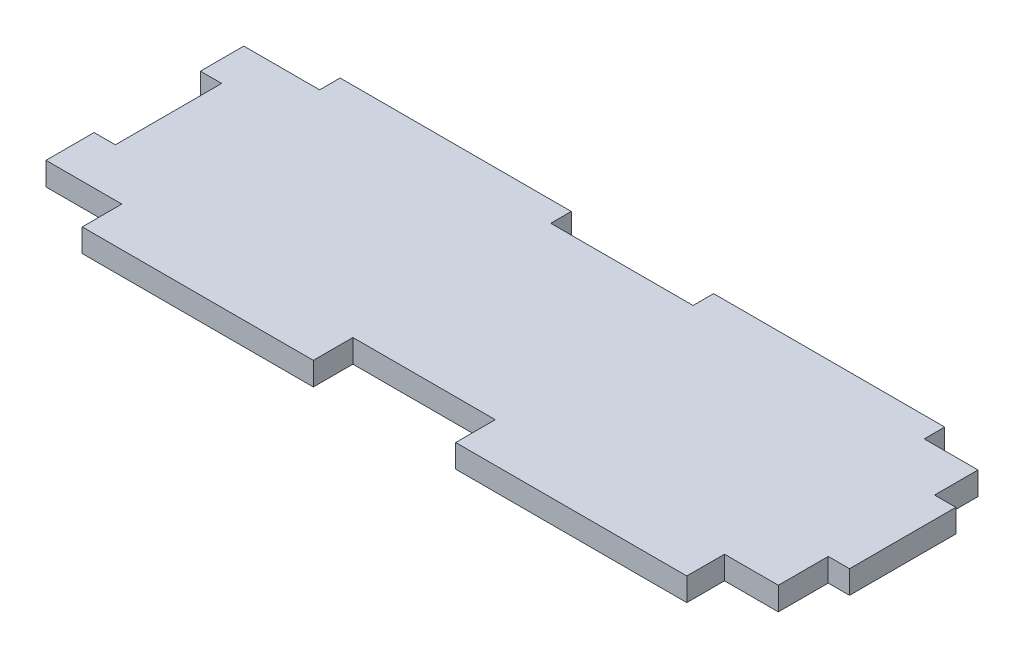
SolidWorks part; units mm, degrees
ref_plane "Front Plane" through (0, 0, 0) normal (0, 0, 1) x (1, 0, 0)
ref_plane "Top Plane" through (0, 0, 0) normal (0, 1, 0) x (1, 0, 0)
ref_plane "Right Plane" through (0, 0, 0) normal (1, 0, 0) x (0, 0, -1)
sketch "Sketch1" plane through (0, 0, 0) normal (0, 1, 0) x (1, 0, 0)
  line L0 (-49.022, -7.3025) -> (-49.022, 7.3025)
  line L1 (-49.022, 7.3025) -> (-51.943, 7.3025)
  line L2 (-51.943, 7.3025) -> (-51.943, 13.9065)
  line L3 (-51.943, 13.9065) -> (-41.529, 13.9065)
  line L4 (-41.529, 13.9065) -> (-41.529, 16.7259)
  line L5 (-41.529, 16.7259) -> (-9.779, 16.7259)
  line L6 (-9.779, 16.7259) -> (-9.779, 13.9065)
  line L7 (-9.779, 13.9065) -> (9.779, 13.9065)
  line L8 (9.779, 13.9065) -> (9.779, 16.7259)
  line L9 (9.779, 16.7259) -> (41.529, 16.7259)
  line L10 (41.529, 16.7259) -> (41.529, 14.1605)
  line L11 (41.529, 14.1605) -> (48.9204, 14.1605)
  line L12 (48.9204, 14.1605) -> (48.9204, 7.3025)
  line L13 (48.9204, 7.3025) -> (51.8414, 7.3025)
  line L14 (51.8414, 7.3025) -> (51.8414, -7.3025)
  line L15 (-1000, 0) -> (49000, 0) construction
  line L16 (0, -1000) -> (0, 49000) construction
  line L17 (41.528, -19.5961) -> (41.529, -14.1605)
  line L18 (9.779, -13.9065) -> (9.779, -19.3421)
  line L19 (48.9204, -7.3025) -> (51.8414, -7.3025)
  line L20 (48.9204, -14.1605) -> (48.9204, -7.3025)
  line L21 (41.529, -14.1605) -> (48.9204, -14.1605)
  line L22 (9.779, -19.3421) -> (41.528, -19.5961)
  line L23 (-9.779, -13.9065) -> (9.779, -13.9065)
  line L24 (-9.779, -19.3421) -> (-9.779, -13.9065)
  line L25 (-41.529, -19.3421) -> (-9.779, -19.3421)
  line L26 (-41.529, -13.9065) -> (-41.529, -19.3421)
  line L27 (-51.943, -13.9065) -> (-41.529, -13.9065)
  line L28 (-51.943, -7.3025) -> (-51.943, -13.9065)
  line L29 (-49.022, -7.3025) -> (-51.943, -7.3025)
  point P26 (51.8414, 0)
  point P35 (-49.022, 0)
  dimension "D1" = 2.8194
  dimension "D2" = 6.604
  dimension "D3" = 7.3025
  dimension "D4" = 6.858
  dimension "D5" = 7.3025
  dimension "D6" = 2.921
  dimension "D7" = 10.414
  dimension "D8" = 31.75
  dimension "D9" = 31.75
  dimension "D10" = 19.558
  dimension "D11" = 2.921
  dimension "D12" = 7.3914
  dimension "D13" = 49.022
  dimension "D14" = 31.75
  dimension "D15" = 31.75
  dimension "D16" = 5.4356
  dimension "D17" = 5.4356
  dimension "D18" = 5.4356
  dimension "D19" = 5.4356
extrude "Boss-Extrude1" add sketch "Sketch1" along normal mid plane 3.175
sketch "Sketch2" plane through (0, 1.5875, 0) normal (0, 1, 0) x (1, 0, 0)
  line L0 (-51.943, 13.9065) -> (-51.943, 7.3025) construction
  line L1 (-41.529, 13.9065) -> (-51.943, 13.9065)
  line L2 (-41.529, 13.9065) -> (-41.529, 13.2715)
  line L3 (-41.529, 13.2715) -> (-51.943, 13.2715)
  line L4 (-51.943, 13.9065) -> (-51.943, 13.2715)
  line L5 (48.9204, 7.3025) -> (48.9204, 14.1605) construction
  line L6 (9.779, 13.9065) -> (-9.779, 13.9065)
  line L7 (9.779, 13.9065) -> (9.779, 13.2715)
  line L8 (9.779, 13.2715) -> (-9.779, 13.2715)
  line L9 (-9.779, 13.9065) -> (-9.779, 13.2715)
  line L10 (41.529, 14.1605) -> (48.9204, 14.1605)
  line L11 (41.529, 14.1605) -> (41.529, 13.2715)
  line L12 (41.529, 13.2715) -> (48.9204, 13.2715)
  line L13 (48.9204, 14.1605) -> (48.9204, 13.2715)
  line L14 (-9.779, 13.9065) -> (-9.779, 16.7259) construction
  dimension "D1" = 0.635
extrude "Cut-Extrude1" cut sketch "Sketch2" against normal through all
sketch "Sketch3" plane through (0, 1.5875, 0) normal (0, 1, 0) x (1, 0, 0)
  line L1 (-41.529, 16.7259) -> (-41.529, 13.2715) construction
  line L2 (-9.779, 16.7259) -> (-41.529, 16.7259)
  line L3 (-9.779, 16.7259) -> (-9.779, 16.0909)
  line L4 (-9.779, 16.0909) -> (-41.529, 16.0909)
  line L6 (9.779, -19.3421) -> (41.528, -19.3421)
  line L7 (41.528, -19.5961) -> (41.529, -14.1605) construction
  line L8 (41.528, -19.3421) -> (41.528, -19.5961)
  line L9 (41.528, -19.5961) -> (9.7791, -19.5961)
  line L11 (9.7791, -19.5961) -> (9.779, -19.3421)
  line L12 (-41.529, 16.7259) -> (-41.529, 16.0909)
  line L13 (41.529, 13.2715) -> (41.529, 16.7259) construction
  line L14 (9.779, 16.7259) -> (41.529, 16.7259)
  line L15 (9.779, 16.7259) -> (9.779, 16.0909)
  line L16 (9.779, 16.0909) -> (41.529, 16.0909)
  line L17 (41.529, 16.7259) -> (41.529, 16.0909)
  dimension "D1" = 0.635
extrude "Cut-Extrude3" cut sketch "Sketch3" against normal through all
